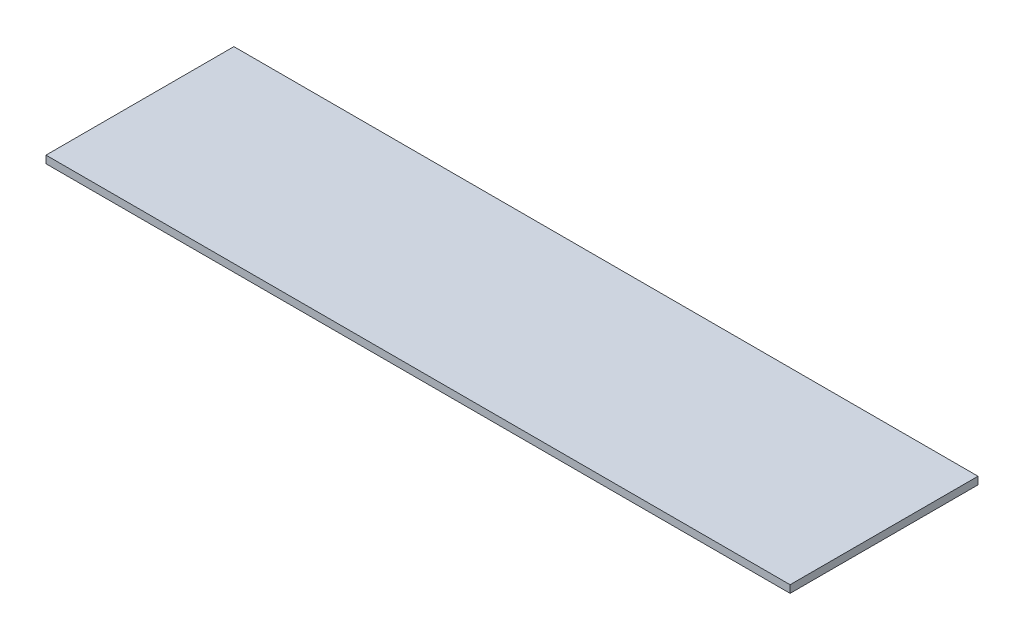
SolidWorks part; units mm, degrees
material "Бук"
ref_plane "Спереди" through (0, 0, 0) normal (0, 0, 1) x (1, 0, 0)
ref_plane "Сверху" through (0, 0, 0) normal (0, 1, 0) x (1, 0, 0)
ref_plane "Справа" through (0, 0, 0) normal (1, 0, 0) x (0, 0, -1)
sketch "Эскиз1" plane through (0, 0, 0) normal (0, 1, 0) x (1, 0, 0)
  line L1 (0, 0) -> (990, 0)
  line L2 (0, 0) -> (0, 250)
  line L3 (0, 250) -> (990, 250)
  line L4 (990, 0) -> (990, 250)
  dimension "D1" = 250
  dimension "D2" = 990
extrude "Бобышка-Вытянуть1" add sketch "Эскиз1" along normal blind 10
